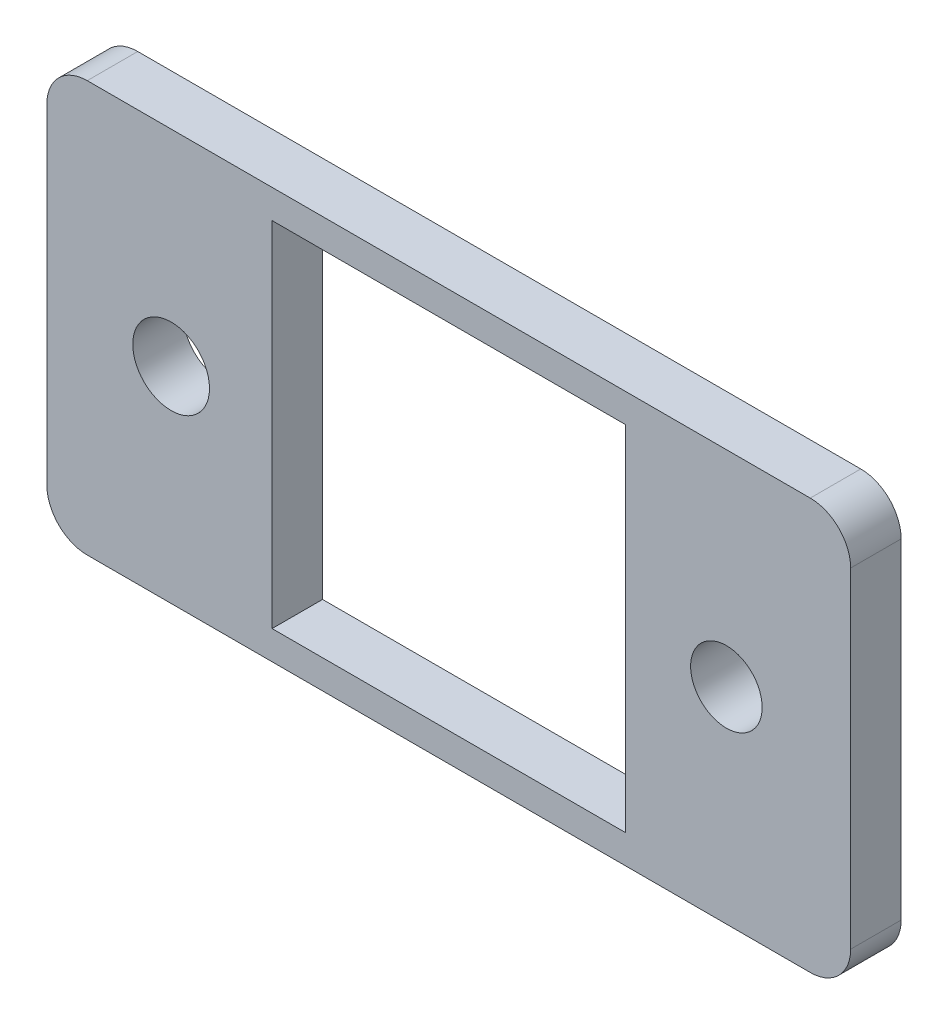
SolidWorks part; units mm, degrees
material "Plain Carbon Steel"
ref_plane "Front Plane" through (0, 0, 0) normal (0, 0, 1) x (1, 0, 0)
ref_plane "Top Plane" through (0, 0, 0) normal (0, 1, 0) x (1, 0, 0)
ref_plane "Right Plane" through (0, 0, 0) normal (1, 0, 0) x (0, 0, -1)
sketch "Sketch1" plane through (0, 0, 0) normal (0, 0, 1) x (1, 0, 0)
  line L1 (-25.2779, -12.9213) -> (25.2779, -12.9213)
  line L2 (-25.2779, -12.9213) -> (-25.2779, 12.9213)
  line L3 (-25.2779, 12.9213) -> (25.2779, 12.9213)
  line L4 (25.2779, -12.9213) -> (25.2779, 12.9213)
  line L5 (-25.2779, -12.9213) -> (25.2779, 12.9213) construction
  line L6 (-25.2779, 12.9213) -> (25.2779, -12.9213) construction
  line L7 (-11.1125, -11.1125) -> (11.1125, -11.1125)
  line L8 (-11.1125, -11.1125) -> (-11.1125, 11.1125)
  line L9 (-11.1125, 11.1125) -> (11.1125, 11.1125)
  line L10 (11.1125, -11.1125) -> (11.1125, 11.1125)
  line L11 (-11.1125, -11.1125) -> (11.1125, 11.1125) construction
  line L12 (-11.1125, 11.1125) -> (11.1125, -11.1125) construction
  circle A0 centre (-17.4625, 0) radius 2.413
  circle A1 centre (17.4625, 0) radius 2.2498
  circle A2 centre (0, 0) radius 6.35
  dimension "D1" = 50.5557
  dimension "D2" = 25.8426
  dimension "D3" = 22.225
  dimension "D4" = 22.225
extrude "Boss-Extrude1" add sketch "Sketch1" along normal blind 3.175 contours L1 L4 L3 L2 A1 A0 L10 L7 L8 L9
fillet "Fillet1" radius 2.54 4 edges at (-25.2779, -12.9213, 1.5875) (25.2779, -12.9213, 1.5875) (25.2779, 12.9213, 1.5875) (-25.2779, 12.9213, 1.5875)
